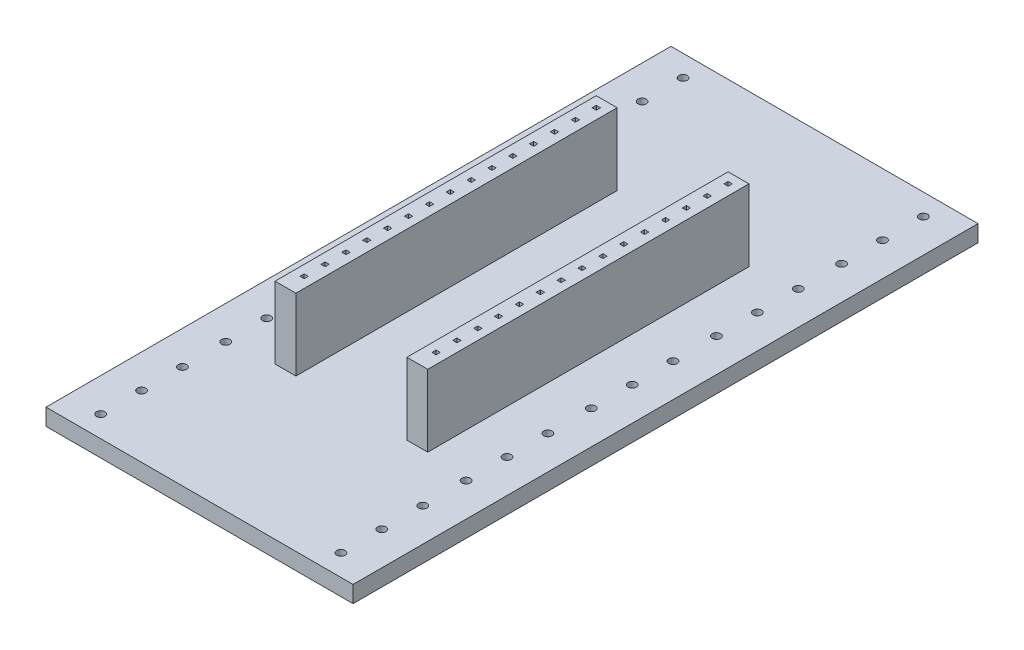
SolidWorks part; units mm, degrees
ref_plane "Alzado" through (0, 0, 0) normal (0, 0, 1) x (1, 0, 0)
ref_plane "Planta" through (0, 0, 0) normal (0, 1, 0) x (1, 0, 0)
ref_plane "Vista lateral" through (0, 0, 0) normal (1, 0, 0) x (0, 0, -1)
sketch "Croquis1" plane through (0, 0, 0) normal (0, 1, 0) x (1, 0, 0)
  line L1 (-18.4, 37.45) -> (18.4, 37.45)
  line L2 (-18.4, 37.45) -> (-18.4, -37.45)
  line L3 (-18.4, -37.45) -> (18.4, -37.45)
  line L4 (18.4, 37.45) -> (18.4, -37.45)
  line L5 (-18.4, 37.45) -> (18.4, -37.45) construction
  line L6 (-18.4, -37.45) -> (18.4, 37.45) construction
  point P0 (0, 0)
  dimension "D1" = 74.9
  dimension "D2" = 36.8
extrude "Saliente-Extruir1" add sketch "Croquis1" along normal blind 2
sketch "Croquis3" plane through (0, 2, 0) normal (0, 1, 0) x (1, 0, 0)
  line L0 (18.4, 37.45) -> (-18.4, 37.45) construction
  line L1 (-18.4, 37.45) -> (-18.4, -37.45) construction
  circle A0 centre (-14.4, 34.9) radius 0.5
  dimension "D1" = 1
  dimension "D2" = 2.55
  dimension "D3" = 4
extrude "Cortar-Extruir1" cut sketch "Croquis3" against normal up to surface (2 mm away) up to face at (0, 0, 0)
pattern_linear "MatrizL1" count 2 spacing 28.8 along (1, 0, 0) count 3 spacing 4.9 along (0, 0, 1) of "Cortar-Extruir1"
sketch "Croquis4" plane through (0, 2, 0) normal (0, 1, 0) x (1, 0, 0)
  line L0 (-18.4, 37.45) -> (-18.4, -37.45) construction
  line L1 (-9.15, 19.25) -> (-6.65, 19.25)
  line L2 (-9.15, 19.25) -> (-9.15, -19.25)
  line L3 (-9.15, -19.25) -> (-6.65, -19.25)
  line L4 (-6.65, 19.25) -> (-6.65, -19.25)
  line L5 (-9.15, 19.25) -> (-6.65, -19.25) construction
  line L6 (-9.15, -19.25) -> (-6.65, 19.25) construction
  line L7 (18.4, -37.45) -> (18.4, 37.45) construction
  line L8 (6.65, 19.25) -> (9.15, 19.25)
  line L9 (6.65, 19.25) -> (6.65, -19.25)
  line L10 (6.65, -19.25) -> (9.15, -19.25)
  line L11 (9.15, 19.25) -> (9.15, -19.25)
  line L12 (6.65, 19.25) -> (9.15, -19.25) construction
  line L13 (6.65, -19.25) -> (9.15, 19.25) construction
  point P0 (-7.9, 0)
  point P9 (7.9, 0)
  point P15 (0, 0)
  point P16 (0, 0)
  dimension "D1" = 2.5
  dimension "D2" = 38.5
  dimension "D3" = 10.5
  dimension "D4" = 10.5
  dimension "D5" = 2.5
extrude "Saliente-Extruir2" add sketch "Croquis4" along normal blind 8.6
sketch "Croquis5" plane through (0, 10.6, 0) normal (0, 1, 0) x (1, 0, 0)
  line L0 (-6.65, 19.25) -> (-9.15, 19.25) construction
  line L1 (-8.15, 18.25) -> (-7.65, 18.25)
  line L2 (-8.15, 18.25) -> (-8.15, 17.75)
  line L3 (-8.15, 17.75) -> (-7.65, 17.75)
  line L4 (-7.65, 18.25) -> (-7.65, 17.75)
  line L5 (-8.15, 18.25) -> (-7.65, 17.75) construction
  line L6 (-8.15, 17.75) -> (-7.65, 18.25) construction
  point P0 (-7.9, 18)
  point P7 (-7.9, 19.25)
  dimension "D1" = 0.5
  dimension "D2" = 0.5
  dimension "D3" = 1.25
extrude "Cortar-Extruir2" cut sketch "Croquis5" against normal blind 6
pattern_linear "MatrizL5" count 2 spacing 15.8 along (1, 0, 0) count 15 spacing 2.5 along (0, 0, 1) of "Cortar-Extruir2"
pattern_linear "MatrizL6" count 5 spacing 15 along (0, 0, 1) of "MatrizL1", "Cortar-Extruir1"
